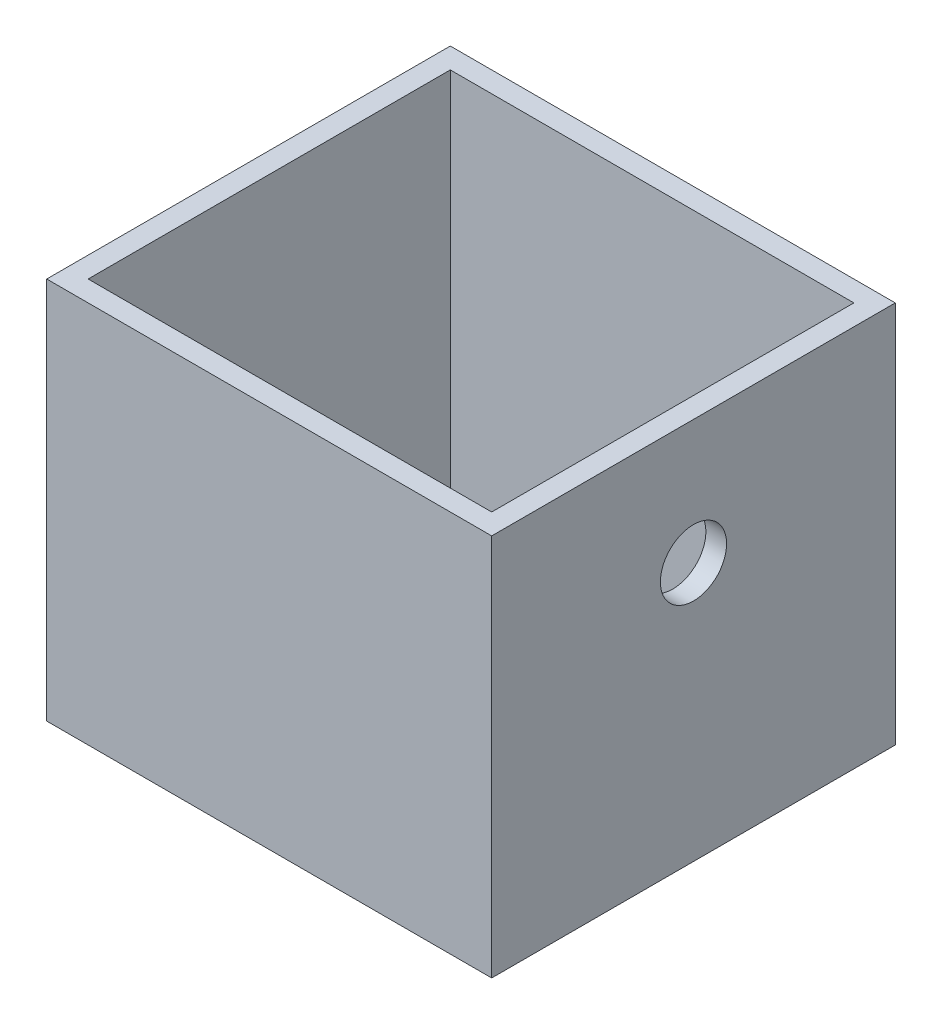
SolidWorks part; units mm, degrees
ref_plane "Front Plane" through (0, 0, 0) normal (0, 0, 1) x (1, 0, 0)
ref_plane "Top Plane" through (0, 0, 0) normal (0, 1, 0) x (1, 0, 0)
ref_plane "Right Plane" through (0, 0, 0) normal (1, 0, 0) x (0, 0, -1)
sketch "Sketch1" plane through (0, 0, 0) normal (0, 1, 0) x (1, 0, 0)
  line L1 (-215, 195) -> (215, 195)
  line L2 (-215, 195) -> (-215, -195)
  line L3 (-215, -195) -> (215, -195)
  line L4 (215, 195) -> (215, -195)
  line L5 (-215, 195) -> (215, -195) construction
  line L6 (-215, -195) -> (215, 195) construction
  point P0 (0, 0)
  dimension "D1" = 390
  dimension "D2" = 430
extrude "Boss-Extrude1" add sketch "Sketch1" along normal blind 370
shell "Shell1" thickness 20
sketch "Sketch2" plane through (215, 0, 0) normal (1, 0, 0) x (0, 0, -1)
  circle A0 centre (0, 250) radius 32
other "AlignGroup1"
other "AlignGroup2"
extrude "Cut-Extrude2" cut sketch "Sketch2" against normal up to body separate body
